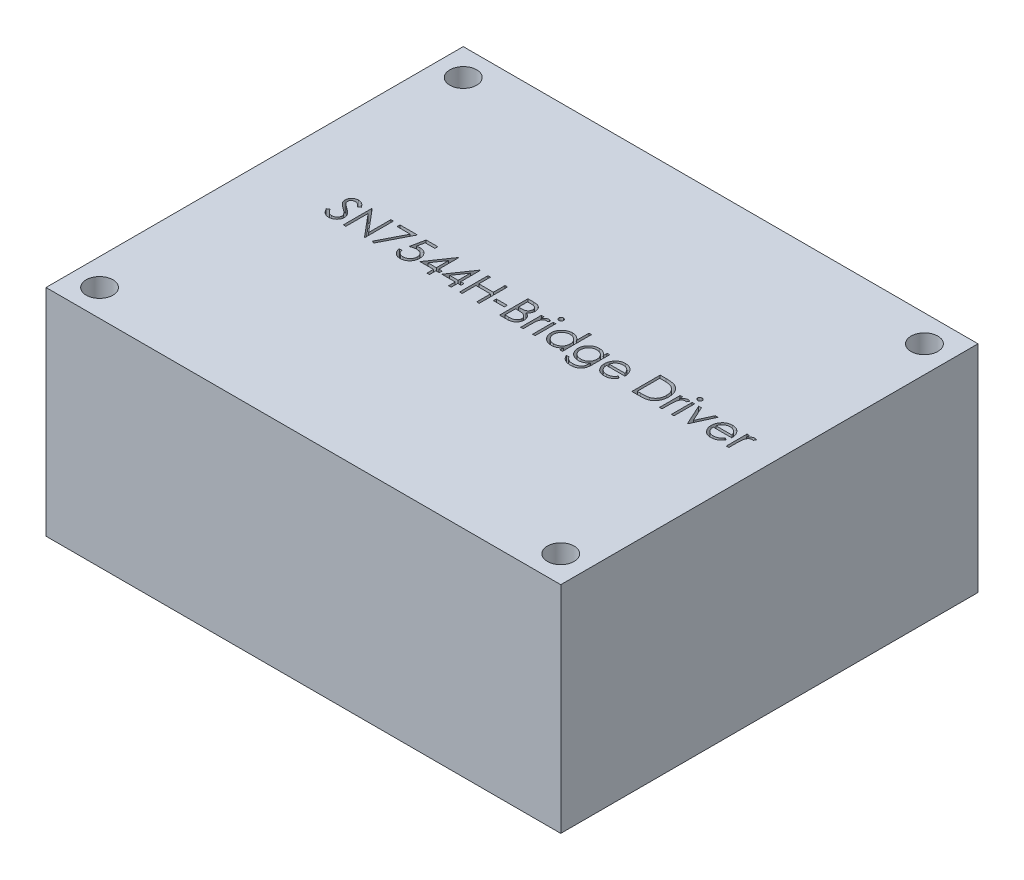
SolidWorks part; units mm, degrees
ref_plane "Front Plane" through (0, 0, 0) normal (0, 0, 1) x (1, 0, 0)
ref_plane "Top Plane" through (0, 0, 0) normal (0, 1, 0) x (1, 0, 0)
ref_plane "Right Plane" through (0, 0, 0) normal (1, 0, 0) x (0, 0, -1)
sketch "Sketch1" plane through (0, 0, 0) normal (0, 1, 0) x (1, 0, 0)
  line L1 (0, 0) -> (57.658, 0)
  line L2 (0, 0) -> (0, 46.736)
  line L3 (0, 46.736) -> (57.658, 46.736)
  line L4 (57.658, 0) -> (57.658, 46.736)
  dimension "D1" = 57.658
  dimension "D2" = 46.736
extrude "Boss-Extrude1" add sketch "Sketch1" along normal blind 24.13
sketch "Sketch2" plane through (0, 24.13, 0) normal (0, 1, 0) x (1, 0, 0)
  line L0 (28.829, 46.736) -> (28.829, 0) construction
  line L1 (57.658, 46.736) -> (0, 46.736) construction
  line L2 (0, 0) -> (57.658, 0) construction
  line L3 (0, 23.368) -> (57.658, 23.368) construction
  line L4 (0, 46.736) -> (0, 0) construction
  line L5 (57.658, 0) -> (57.658, 46.736) construction
  circle A0 centre (3, 43.736) radius 1.5
  circle A1 centre (3, 3) radius 1.5
  circle A2 centre (54.658, 3) radius 1.5
  circle A3 centre (54.658, 43.736) radius 1.5
  point P14 (0, 0)
  point P16 (0, 0)
  dimension "D1" = 3
  dimension "D2" = 3
  dimension "D3" = 3
extrude "Cut-Extrude1" cut sketch "Sketch2" against normal through all
sketch "Sketch3" plane through (0, 24.13, 0) normal (0, 1, 0) x (1, 0, 0)
  text T0 "SN7544H-Bridge Driver"
extrude "Cut-Extrude2" cut sketch "Sketch3" against normal blind 1.27
